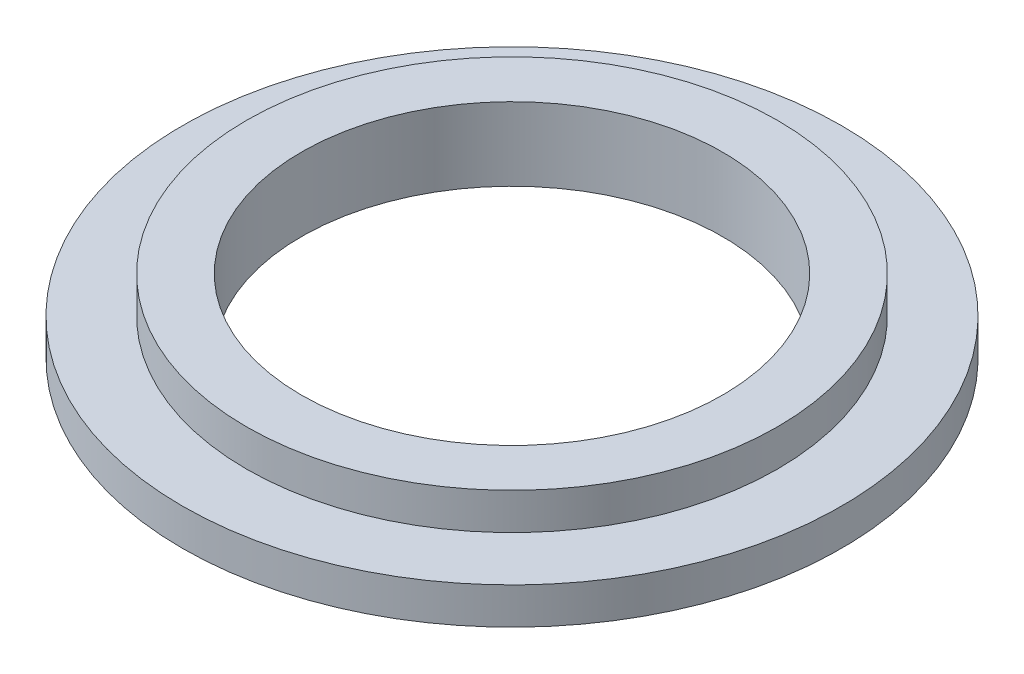
SolidWorks part; units mm, degrees
ref_plane "Front Plane" through (0, 0, 0) normal (0, 0, 1) x (1, 0, 0)
ref_plane "Top Plane" through (0, 0, 0) normal (0, 1, 0) x (1, 0, 0)
ref_plane "Right Plane" through (0, 0, 0) normal (1, 0, 0) x (0, 0, -1)
sketch "Sketch1" plane through (0, 0, 0) normal (0, 1, 0) x (1, 0, 0)
  circle A1 centre (0, 0) radius 18
  dimension "D1" = 36
extrude "Boss-Extrude1" add sketch "Sketch1" along normal blind 2
sketch "Sketch2" plane through (0, 2, 0) normal (0, 1, 0) x (1, 0, 0)
  circle A0 centre (0, 0) radius 14.5
  dimension "D1" = 29
extrude "Boss-Extrude2" add sketch "Sketch2" along normal blind 2
sketch "Sketch3" plane through (0, 0, 0) normal (0, 1, 0) x (1, 0, 0)
  circle A0 centre (0, 0) radius 11.5
  dimension "D1" = 23
extrude "Cut-Extrude3" cut sketch "Sketch3" against normal through all and the other way through all
equation "\"stopper_dia\"= 36mm"
equation "\"D1@Sketch1\"=\"stopper_dia\""
equation "\"hole_dia\"= 23mm"
equation "\"D1@Sketch3\"=\"hole_dia\""
